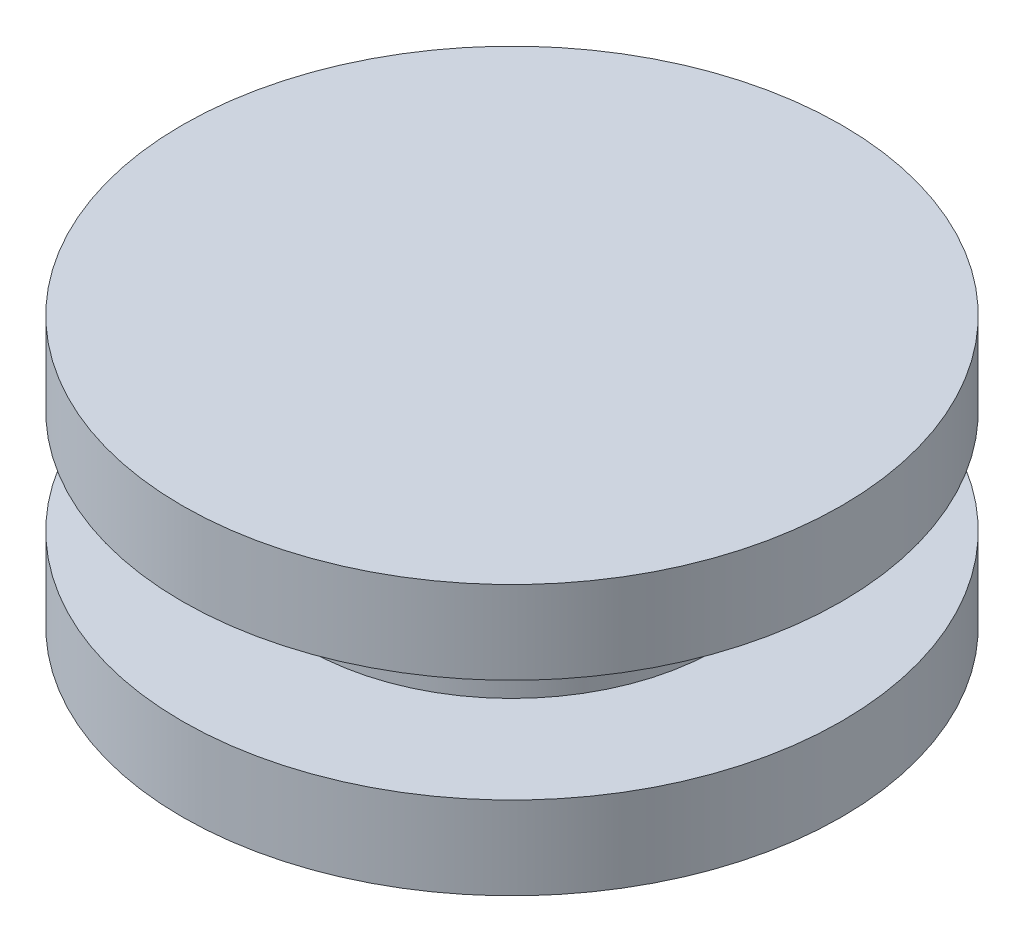
SolidWorks part; units mm, degrees
ref_plane "Front Plane" through (0, 0, 0) normal (0, 0, 1) x (1, 0, 0)
ref_plane "Top Plane" through (0, 0, 0) normal (0, 1, 0) x (1, 0, 0)
ref_plane "Right Plane" through (0, 0, 0) normal (1, 0, 0) x (0, 0, -1)
sketch "Sketch1" plane through (0, 0, 0) normal (0, 1, 0) x (1, 0, 0)
  circle A0 centre (0, 0) radius 2.475
  dimension "D1" = 4.95
extrude "Boss-Extrude1" add sketch "Sketch1" along normal mid plane 1.25
sketch "Sketch3" plane through (0, 0.625, 0) normal (0, 1, 0) x (1, 0, 0)
  circle A2 centre (0, 0) radius 3.975
  circle A3 centre (0, 0) radius 3.975
  dimension "D1" = 1.5
extrude "Boss-Extrude2" add sketch "Sketch3" along normal blind 1
mirror "Mirror1" about plane through (0, 0, 0) normal (0, 1, 0) of "Boss-Extrude2"
